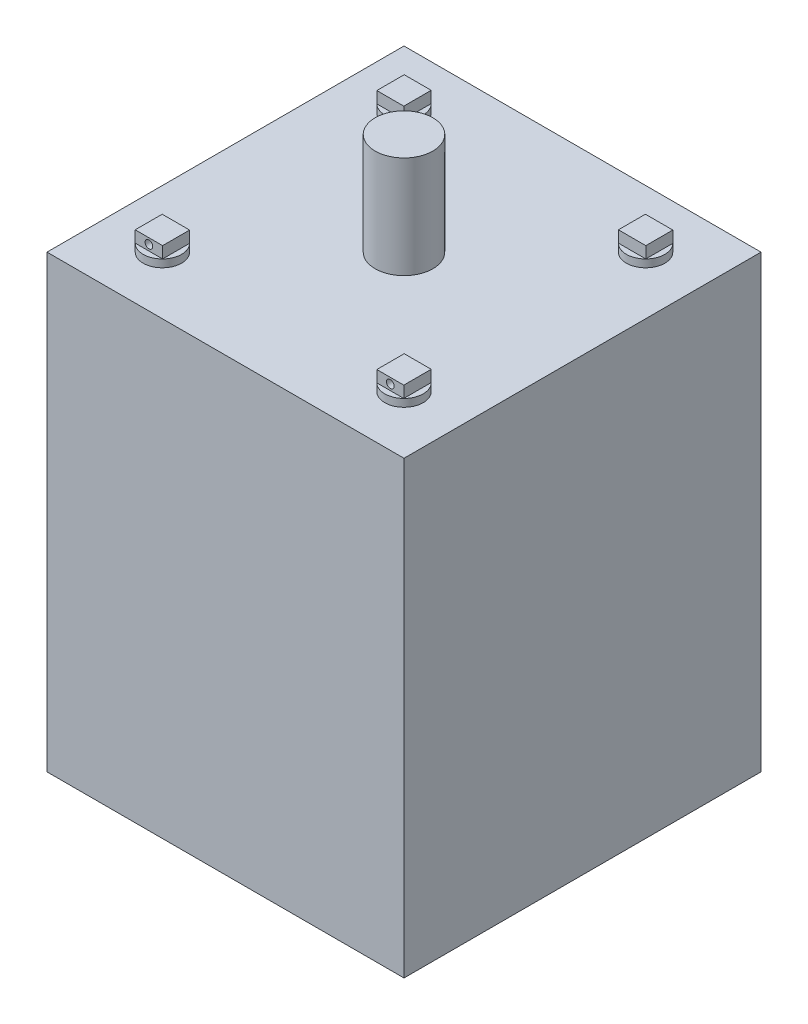
SolidWorks part; units mm, degrees
ref_plane "Front Plane" through (0, 0, 0) normal (0, 0, 1) x (1, 0, 0)
ref_plane "Top Plane" through (0, 0, 0) normal (0, 1, 0) x (1, 0, 0)
ref_plane "Right Plane" through (0, 0, 0) normal (1, 0, 0) x (0, 0, -1)
sketch "Sketch1" plane through (0, 0, 0) normal (0, 1, 0) x (1, 0, 0)
  line L1 (0, 0) -> (92.8, 0)
  line L2 (0, 0) -> (0, 92.8)
  line L3 (0, 92.8) -> (92.8, 92.8)
  line L4 (92.8, 0) -> (92.8, 92.8)
  dimension "D1" = 92.8
extrude "Boss-Extrude1" add sketch "Sketch1" along normal blind 117
sketch "Sketch2" plane through (0, 117, 0) normal (0, 1, 0) x (1, 0, 0)
  line L0 (46.4, 0) -> (46.4, 92.8) construction
  line L4 (0, 92.8) -> (0, 0)
  line L5 (0, 0) -> (92.8, 0)
  line L6 (92.8, 0) -> (92.8, 92.8)
  line L7 (92.8, 92.8) -> (0, 92.8)
  line L8 (0, 92.8) -> (0, 0)
  line L9 (0, 0) -> (92.8, 0)
  line L10 (92.8, 0) -> (92.8, 92.8)
  line L11 (92.8, 92.8) -> (0, 92.8)
  circle A0 centre (46.4, 46.4) radius 7.5
  dimension "D1" = 0
extrude "Boss-Extrude2" add sketch "Sketch2" along normal blind 143.5 from surface at -117 contours A0 starting at face at (46.4, 0, -46.4)
sketch "Sketch3" plane through (0, 117, 0) normal (0, 1, 0) x (1, 0, 0)
  line L0 (77.8, 77.8) -> (15, 77.8)
  line L1 (15, 77.8) -> (15, 15)
  line L2 (15, 15) -> (77.8, 15)
  line L3 (77.8, 15) -> (77.8, 77.8)
  line L4 (0, 92.8) -> (0, 0)
  line L5 (0, 0) -> (92.8, 0)
  line L6 (92.8, 0) -> (92.8, 92.8)
  line L7 (92.8, 92.8) -> (0, 92.8)
  line L8 (0, 92.8) -> (0, 0)
  line L9 (0, 0) -> (92.8, 0)
  line L10 (92.8, 0) -> (92.8, 92.8)
  line L11 (92.8, 92.8) -> (0, 92.8)
  circle A0 centre (15, 77.8) radius 5
  dimension "D1" = 0
  dimension "D2" = 15
extrude "Boss-Extrude3" add sketch "Sketch3" along normal blind 2 contours L0 A0 L1 | L1 A0 L0
sketch "Sketch4" plane through (0, 119, 0) normal (0, 1, 0) x (1, 0, 0)
  line L1 (18.5089, 81.3619) -> (11.4911, 81.3619)
  line L2 (18.5089, 81.3619) -> (18.5089, 74.2381)
  line L3 (18.5089, 74.2381) -> (11.4911, 74.2381)
  line L4 (11.4911, 81.3619) -> (11.4911, 74.2381)
  line L5 (18.5089, 81.3619) -> (11.4911, 74.2381) construction
  line L6 (18.5089, 74.2381) -> (11.4911, 81.3619) construction
  circle A1 centre (15, 77.8) radius 5
  circle A2 centre (15, 77.8) radius 5
  dimension "D1" = 0
extrude "Boss-Extrude4" add sketch "Sketch4" along normal blind 3 contours L1 L4 L3 L2
sketch "Sketch5" plane through (0, 0, -81.3619) normal (0, 0, -1) x (-1, 0, 0)
  line L0 (-18.5089, 120.5) -> (-11.4911, 120.5) construction
  line L4 (-18.5089, 119) -> (-11.4911, 119)
  line L5 (-11.4911, 119) -> (-11.4911, 122)
  line L6 (-11.4911, 122) -> (-18.5089, 122)
  line L7 (-18.5089, 122) -> (-18.5089, 119)
  line L8 (-18.5089, 119) -> (-11.4911, 119)
  line L9 (-11.4911, 119) -> (-11.4911, 122)
  line L10 (-11.4911, 122) -> (-18.5089, 122)
  line L11 (-18.5089, 122) -> (-18.5089, 119)
  circle A0 centre (-15, 120.5) radius 1
  dimension "D1" = 0
extrude "Cut-Extrude1" cut sketch "Sketch5" against normal blind 3.5 contours A0
pattern_circular "CirPattern1" count 4 over 360 about axis through (46.4, 0, -46.4) along (0, 1, 0) of "Boss-Extrude4", "Boss-Extrude3"
ref_plane "Plane1" through (0, 0, -46.4) normal (0, 0, -1) x (-1, 0, 0)
ref_plane "Plane2" through (46.4, 0, 0) normal (1, 0, 0) x (0, 0, -1)
mirror "Mirror1" about plane through (0, 0, -46.4) normal (0, 0, -1) of "Cut-Extrude1"
mirror "Mirror2" about plane through (46.4, 0, 0) normal (1, 0, 0) of "Cut-Extrude1" second plane through (0, 0, -46.4) second plane normal (0, 0, -1)
